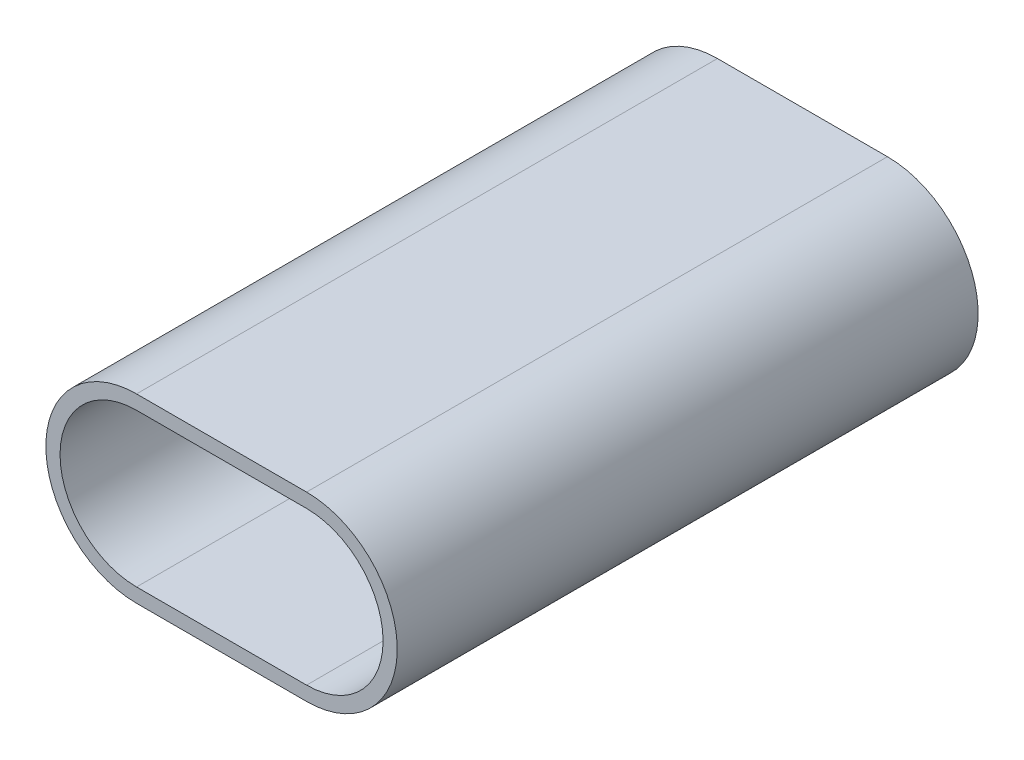
SolidWorks part; units mm, degrees
material "ABS"
ref_plane "Front Plane" through (0, 0, 0) normal (0, 0, 1) x (1, 0, 0)
ref_plane "Top Plane" through (0, 0, 0) normal (0, 1, 0) x (1, 0, 0)
ref_plane "Right Plane" through (0, 0, 0) normal (1, 0, 0) x (0, 0, -1)
sketch "ProfileS" plane through (0, 0, 0) normal (0, 0, 1) x (1, 0, 0)
  line L0 (-3, 0) -> (3, 0) construction
  line L1 (-3, 3.2) -> (3, 3.2)
  line L2 (-3, -3.2) -> (3, -3.2)
  arc A0 (-3, 3.2) -> (-3, -3.2) centre (-3, 0) ccw
  arc A1 (3, -3.2) -> (3, 3.2) centre (3, 0) ccw
  point P2 (0, 0)
  point P8 (-6.2, 0)
  point P9 (6.2, 0)
  dimension "Height" = 6.4
  dimension "Width" = 12.4
extrude "Profile" add sketch "ProfileS" along normal mid plane 20.5
sketch "PocketS" plane through (0, 0, 10.25) normal (0, 0, 1) x (1, 0, 0)
  line L4 (-3, -2.7) -> (3, -2.7)
  line L5 (3, 2.7) -> (-3, 2.7)
  line L6 (-3, -2.7) -> (3, -2.7)
  line L7 (3, 2.7) -> (-3, 2.7)
  arc A4 (-3, 2.7) -> (-3, -2.7) centre (-3, 0) ccw
  arc A5 (3, -2.7) -> (3, 2.7) centre (3, 0) ccw
  arc A6 (-3, 2.7) -> (-3, -2.7) centre (-3, 0) ccw
  arc A7 (3, -2.7) -> (3, 2.7) centre (3, 0) ccw
  dimension "WallThickness" = 0.5
extrude "Pocket" cut sketch "PocketS" against normal offset from surface (19.5 mm away) 1 up to face at (0, 0, -10.25)
sketch "HoleS" plane through (0, 0, -10.25) normal (0, 0, -1) x (-1, 0, 0)
  circle A0 centre (0, 0) radius 2
  dimension "Diameter" = 4
extrude "Hole" cut sketch "HoleS" against normal up to surface (1 mm away) up to face at (0, 0, -9.25)
